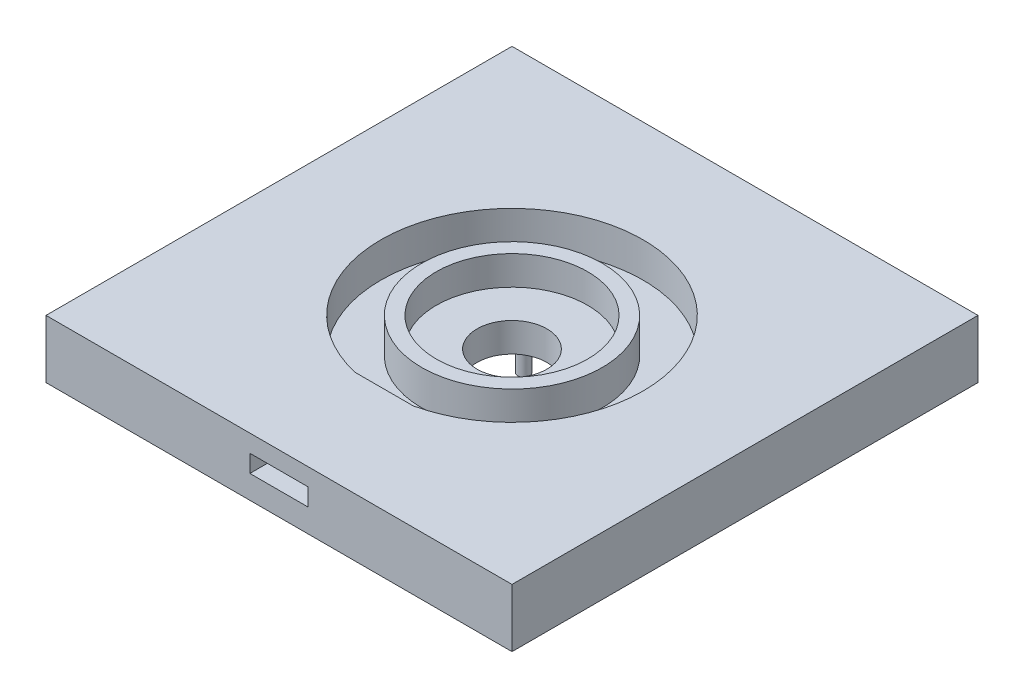
SolidWorks part; units mm, degrees
ref_plane "Front Plane" through (0, 0, 0) normal (0, 0, 1) x (1, 0, 0)
ref_plane "Top Plane" through (0, 0, 0) normal (0, 1, 0) x (1, 0, 0)
ref_plane "Right Plane" through (0, 0, 0) normal (1, 0, 0) x (0, 0, -1)
sketch "Sketch28" plane through (0, 0, 0) normal (0, 1, 0) x (1, 0, 0)
  line L1 (-38.0554, -35.7587) -> (41.9446, -35.7587)
  line L2 (-38.0554, -35.7587) -> (-38.0554, 44.2413)
  line L3 (-38.0554, 44.2413) -> (41.9446, 44.2413)
  line L4 (41.9446, -35.7587) -> (41.9446, 44.2413)
  dimension "D1" = 80
extrude "Boss-Extrude1" add sketch "Sketch28" along normal blind 10
hole_wizard "CBORE for M10 Cheese Head Screw1" positions "Sketch30" profile "Sketch29" counterbore size "M10" standard "AS" end condition through all
sketch "Sketch30" plane through (0, 10, 0) normal (0, 1, 0) x (1, 0, 0)
  point P0 (1.9446, 4.2413)
sketch "Sketch29" plane through (1.9446, 10, -4.2413) normal (1, 0, 0) x (0, 0, 1)
  line L0 (0, 0) -> (0, 10)
  line L1 (0, 10) -> (6, 10)
  line L3 (6, 10) -> (6, 5)
  line L4 (6, 5) -> (13, 5)
  line L5 (13, 5) -> (13, 0)
  line L7 (13, 0) -> (0, 0)
  line L11 (0, -6.35) -> (0, 107.95) construction
  dimension "Thru Hole Dia." = 12
  dimension "Thru Hole Depth" = 10
  dimension "C'Bore Dia." = 26
  dimension "C'Bore Depth" = 5
sketch "Sketch36" plane through (0, 0, 0) normal (0, -1, 0) x (1, 0, 0)
  circle A0 centre (12.4446, -16.7413) radius 1
  circle A1 centre (12.4446, -4.2413) radius 1
  circle A2 centre (-8.5554, -16.7413) radius 1
  circle A3 centre (-8.5554, -4.2413) radius 1
extrude "Boss-Extrude5" add sketch "Sketch36" along normal blind 10
sketch "Sketch37" plane through (0, 10, 0) normal (0, 1, 0) x (1, 0, 0)
  line L0 (1.9446, 44.2413) -> (1.9446, -35.7587) construction
  line L1 (41.9446, 44.2413) -> (-38.0554, 44.2413) construction
  line L2 (-38.0554, -35.7587) -> (41.9446, -35.7587) construction
  line L3 (-38.0554, 4.2413) -> (41.9446, 4.2413) construction
  line L4 (-38.0554, 44.2413) -> (-38.0554, -35.7587) construction
  line L5 (41.9446, -35.7587) -> (41.9446, 44.2413) construction
  circle A0 centre (1.9446, 4.2413) radius 22.5
  circle A1 centre (1.9446, 4.2413) radius 15.5
  dimension "D1" = 31
  dimension "D2" = 45
extrude "Cut-Extrude2" cut sketch "Sketch37" against normal blind 6
sketch "Sketch39" plane through (0, 10, 0) normal (0, 1, 0) x (1, 0, 0)
  line L0 (41.9446, 44.2413) -> (-38.0554, 44.2413) construction
  line L1 (10.8724, 24.8942) -> (-5.6612, 24.8942)
  line L2 (10.8724, 24.8942) -> (10.8724, 44.2413)
  line L3 (10.8724, 44.2413) -> (-5.6612, 44.2413)
  line L4 (-5.6612, 24.8942) -> (-5.6612, 44.2413)
  line L5 (1.9446, -35.7587) -> (6.9446, -35.7587)
  line L6 (-38.0554, -35.7587) -> (41.9446, -35.7587) construction
  line L7 (6.9446, -35.7587) -> (-3.0554, -35.7587)
  line L8 (-3.0554, -35.7587) -> (-3.0554, -17.6961)
  line L9 (-3.0554, -17.6961) -> (6.9446, -17.6961)
  line L10 (6.9446, -17.6961) -> (6.9446, -35.7587)
  circle A0 centre (1.9446, 4.2413) radius 22.5 construction
  circle M5 centre (1.9446, 4.2413) radius 22.5
  line M7 (-38.0554, -35.7587) -> (41.9446, -35.7587)
extrude "Cut-Extrude6" cut sketch "Sketch39" against normal blind 6 contours L10 L8 M5 M7
sketch "Sketch40" plane through (-3.0554, 0, 0) normal (1, 0, 0) x (0, 0, -1)
  line L0 (-35.7587, 4) -> (-35.7587, 10) construction
  line L1 (-35.7587, 7) -> (-17.6961, 7)
  line L2 (-35.7587, 7) -> (-35.7587, 10)
  line L3 (-35.7587, 10) -> (-17.6961, 10)
  line L4 (-17.6961, 7) -> (-17.6961, 10)
extrude "Boss-Extrude7" add sketch "Sketch40" along normal blind 13
